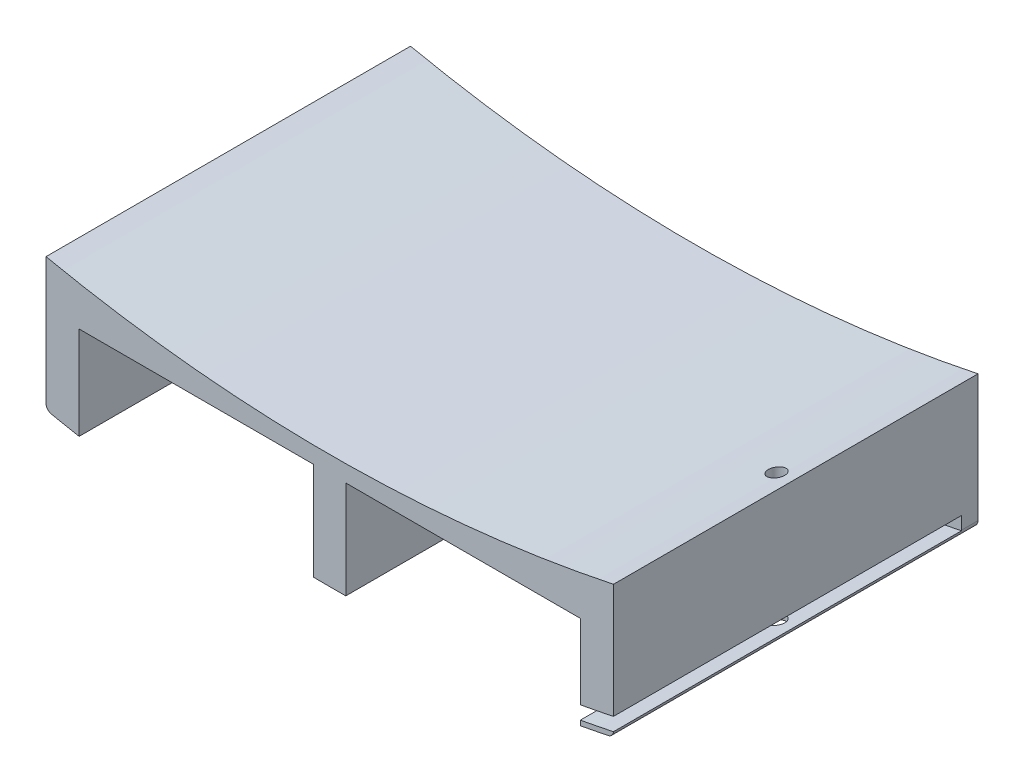
SolidWorks part; units mm, degrees
ref_plane "Front Plane" through (0, 0, 0) normal (0, 0, 1) x (1, 0, 0)
ref_plane "Top Plane" through (0, 0, 0) normal (0, 1, 0) x (1, 0, 0)
ref_plane "Right Plane" through (0, 0, 0) normal (1, 0, 0) x (0, 0, -1)
sketch "ImportedSketch" plane through (0, 0, 0) normal (0, 0, 1) x (1, 0, 0)
  line L9 (-108.7438, 0) -> (-108.7438, -50.8)
  line L11 (-108.7438, 0) -> (-108.7438, 11.3223)
  line L15 (108.7438, 0) -> (108.7438, -50.8)
  line L17 (108.7438, 6.35) -> (108.7438, 0)
  line L18 (108.7438, 6.35) -> (108.7438, 11.3223)
  line L22 (108.7438, 11.3223) -> (108.7438, -50.8)
  line L23 (108.7438, -50.8) -> (-108.7438, -50.8)
  line L24 (108.7438, -50.8) -> (108.7438, 0)
  line L26 (-108.7438, -50.8) -> (-108.7438, 0)
  line L27 (108.7438, -50.8) -> (-108.7438, -50.8)
  line L28 (-108.7438, -50.8) -> (-108.7438, 11.3223)
  arc A0 (-108.7438, 11.3223) -> (108.7438, 11.3223) centre (0, 527.8685) ccw
  point P0 (0, 0)
  point P20 (-108.7438, 11.3223)
sketch "CrossSection" plane through (0, 0, 0) normal (0, 0, 1) x (1, 0, 0)
  line L0 (108.7438, 11.3223) -> (108.7438, -50.8)
  line L1 (108.7438, -50.8) -> (-108.7438, -50.8)
  line L2 (-108.7438, -50.8) -> (-108.7438, 11.3223)
  arc A0 (108.7438, 11.3223) -> (-108.7438, 11.3223) centre (0, 527.8685) cw
extrude "Boss-Extrude2" add sketch "CrossSection" along normal blind 279.4
sketch "Sketch4" plane through (0, 0, 0) normal (0, 0, -1) x (-1, 0, 0)
  line L0 (-108.7438, 11.3223) -> (-108.7437, -39.4777)
  line L1 (108.7438, 11.3223) -> (108.7438, -39.4777)
  line L2 (-108.7437, -39.4777) -> (-108.7438, -50.8)
  line L3 (-108.7438, -50.8) -> (108.7438, -50.8)
  line L4 (108.7438, -50.8) -> (108.7438, -39.4777)
  arc A0 (-108.7438, 11.3223) -> (108.7438, 11.3223) centre (0, 527.8685) ccw
  arc A1 (-108.7437, -39.4777) -> (108.7438, -39.4777) centre (0, 477.0685) ccw
  line M5 (-108.7438, 11.3223) -> (-108.7438, -50.8)
  line M6 (-108.7438, -50.8) -> (108.7438, -50.8)
  line M7 (108.7438, -50.8) -> (108.7438, 11.3223)
  dimension "D1" = 2
extrude "Cut-Extrude1" cut sketch "Sketch4" against normal blind 279.4 contours A1 M5 M6 | A1 L3 M7
fillet "Fillet1" radius 2.54 2 edges at (108.7438, -39.4777, 139.7) (-108.7438, -39.4777, 139.7)
sketch "Sketch5" plane through (0, 0, 279.4) normal (0, 0, 1) x (1, 0, 0)
  line L1 (-108.7438, 11.3223) -> (108.7438, 11.3223)
  line L2 (-108.7438, 11.3223) -> (-108.7438, -50.8)
  line L3 (-108.7438, -50.8) -> (108.7438, -50.8)
  line L4 (108.7438, 11.3223) -> (108.7438, -50.8)
ref_plane "Plane1" through (0, -50.8, 0) normal (0, 1, 0) x (1, 0, 0)
sketch "Sketch7" plane through (0, -50.8, 0) normal (0, 1, 0) x (1, 0, 0)
  line L1 (108.7438, -279.4) -> (-108.7438, -279.4)
  line L2 (108.7438, -279.4) -> (108.7438, 0)
  line L3 (108.7438, 0) -> (-108.7438, 0)
  line L4 (-108.7438, -279.4) -> (-108.7438, 0)
  line L5 (108.7438, -279.4) -> (96.0438, -279.4)
  line L6 (108.7438, -279.4) -> (108.7438, -266.7)
  line L7 (108.7438, -266.7) -> (96.0438, -266.7)
  line L8 (96.0438, -279.4) -> (96.0438, -266.7)
  line L9 (-108.7438, -279.4) -> (-96.0438, -279.4)
  line L10 (-108.7438, -279.4) -> (-108.7438, -266.7)
  line L11 (-108.7438, -266.7) -> (-96.0438, -266.7)
  line L12 (-96.0438, -279.4) -> (-96.0438, -266.7)
  line L13 (-108.7438, 0) -> (-96.0438, 0)
  line L14 (-108.7438, 0) -> (-108.7438, -12.7)
  line L15 (-108.7438, -12.7) -> (-96.0438, -12.7)
  line L16 (-96.0438, 0) -> (-96.0438, -12.7)
  line L17 (108.7438, 0) -> (96.0438, 0)
  line L18 (108.7438, 0) -> (108.7438, -12.7)
  line L19 (108.7438, -12.7) -> (96.0438, -12.7)
  line L20 (96.0438, 0) -> (96.0438, -12.7)
  line L21 (96.0438, -266.7) -> (-96.0438, -266.7)
  line L22 (96.0438, -266.7) -> (96.0438, -12.7)
  line L23 (96.0438, -12.7) -> (-96.0438, -12.7)
  line L24 (-96.0438, -266.7) -> (-96.0438, -12.7)
extrude "Cut-Extrude2" cut sketch "Sketch7" along normal blind 44.45 contours L24 L21 L22 L23
sketch "Sketch8" plane through (0, 0, 12.7) normal (0, 0, 1) x (1, 0, 0)
  line L0 (-96.0438, -41.9891) -> (-96.0438, -6.35)
  line L1 (-96.0438, -6.35) -> (96.0438, -6.35)
  line L2 (96.0438, -6.35) -> (96.0438, -41.9891)
  line L3 (96.0438, -41.9891) -> (-96.0438, -41.9891)
  line L4 (96.0438, -41.9891) -> (-96.0438, -41.9891)
  line L5 (0, -50.8) -> (0, -6.35)
  line L8 (-6.1732, -50.7639) -> (-6.1732, -6.35)
  line L9 (-6.1732, -6.35) -> (6.1732, -6.35)
  line L10 (6.1732, -50.7639) -> (6.1732, -6.35)
  arc A0 (-96.0438, -41.9891) -> (96.0438, -41.9891) centre (0, 477.0685) ccw
  point P11 (0, -41.9891)
extrude "Boss-Extrude3" add sketch "Sketch8" along normal blind 258.064 contours L4 L10 L1 L5 | L8 L4 L5 L1
sketch "Sketch13" plane through (0, 0, 12.7) normal (0, 0, 1) x (1, 0, 0)
  line L0 (0, -50.8) -> (0, -41.9891)
  line L1 (6.1732, -41.9891) -> (-6.1732, -41.9891) construction
  line L2 (-96.0438, -37.5836) -> (-96.0438, -41.9891)
  line L3 (96.0438, -41.9891) -> (96.0438, -37.5836)
  line L4 (-96.0438, -40.1236) -> (-96.0438, -35.0436)
  line L5 (96.0438, -40.1236) -> (96.0438, -35.0436)
  arc A2 (-96.0438, -35.0436) -> (96.0438, -35.0436) centre (0, 484.014) ccw
  arc A3 (-96.0438, -40.1236) -> (96.0438, -40.1236) centre (0, 478.934) ccw
  point P9 (0, -46.3945)
  line M6 (-96.0438, -6.35) -> (-96.0438, -41.9891)
  line M8 (96.0438, -41.9891) -> (96.0438, -6.35)
extrude "Cut-Extrude3" cut sketch "Sketch13" against normal blind 6.35 and the other way blind 260.35 contours A3 L0 A2 M6 | L0 A3 L3 A2 M8
sketch "Sketch14" plane through (0, 0, 266.7) normal (0, 0, -1) x (-1, 0, 0)
  line L0 (96.0438, -35.0436) -> (96.0438, -40.1236)
  line L1 (-150.5419, -27.0129) -> (-150.5419, -21.9329)
  arc A0 (-150.5419, -27.0129) -> (96.0438, -40.1236) centre (0, 478.934) ccw
  arc A1 (-150.5419, -21.9329) -> (96.0438, -35.0436) centre (0, 484.014) ccw
extrude "Cut-Extrude4" cut sketch "Sketch14" against normal blind 6.35 and the other way blind 260.35
sketch "Sketch15" plane through (0, 0, 266.7) normal (0, 0, -1) x (-1, 0, 0)
  line L0 (6.1732, -41.9891) -> (-6.1732, -41.9891)
  line L1 (-6.1732, -6.35) -> (-6.1732, -41.9891) construction
  line L2 (6.1732, -41.9891) -> (-6.1732, -41.9891) construction
  line L3 (6.1732, -41.9891) -> (6.1732, -43.8184)
  line L4 (-6.1732, -41.9891) -> (-6.1732, -43.8184)
  line L5 (6.1732, -41.9891) -> (-6.1732, -41.9891)
  line L6 (6.1732, -43.8184) -> (6.1732, -41.9891)
  line L7 (-6.1732, -41.9891) -> (-6.1732, -43.8184)
  arc A1 (96.0438, -35.0436) -> (-96.0437, -35.0436) centre (0, 484.014) cw
  arc A2 (-96.0438, -35.0436) -> (96.0438, -35.0436) centre (0, 484.014) ccw construction
  arc M2 (-96.0438, -35.0436) -> (96.0438, -35.0436) centre (0, 484.014) ccw
  line M6 (6.1732, -41.9891) -> (-6.1732, -41.9891)
extrude "Boss-Extrude4" add sketch "Sketch15" along normal blind 254 contours L4 L3 M6 M2
sketch "Sketch17" plane through (0, 0, 273.05) normal (0, 0, -1) x (-1, 0, 0)
  line L2 (96.0438, -35.0436) -> (96.0438, -40.1236)
  line L3 (-108.7438, -32.5322) -> (-108.7438, -37.6122)
  arc A0 (96.0438, -35.0436) -> (-108.7438, -32.5322) centre (0, 484.014) cw
  arc A1 (96.0438, -40.1236) -> (-108.7438, -37.6122) centre (0, 478.934) cw
  dimension "D1" = 2
sketch "Sketch18" plane through (0, -50.8, 0) normal (0, 1, 0) x (1, 0, 0)
  line L0 (96.0438, -266.7) -> (106.7173, -279.4)
  line L1 (96.0438, -12.7) -> (106.7173, 0)
  line L3 (96.0438, -139.7) -> (106.7173, -139.7)
  line L4 (96.0438, -266.7) -> (96.0438, -12.7) construction
  line L5 (106.7173, 0) -> (106.7173, -279.4) construction
  circle A0 centre (101.3805, -209.55) radius 3.175
  circle A1 centre (101.3805, -69.85) radius 3.175
  point P16 (101.3805, -69.85)
  point P18 (101.3805, -209.55)
extrude "Cut-Extrude5" cut sketch "Sketch18" along normal blind 71.12 contours A1 | A0
sketch "Sketch19" plane through (108.7438, 0, 0) normal (1, 0, 0) x (0, 0, -1)
  line L0 (-139.7, 11.3223) -> (-139.7, -32.5322) construction
  line L1 (-279.4, 11.3223) -> (0, 11.3223) construction
  line L2 (-6.35, -32.5322) -> (-273.05, -32.5322) construction
sketch "Sketch20" plane through (-108.7438, 0, 0) normal (-1, 0, 0) x (0, 0, 1)
  line L0 (139.7, 11.3223) -> (139.7, -37.4126) construction
  line L1 (279.4, 11.3223) -> (0, 11.3223) construction
  line L2 (0, -37.4126) -> (279.4, -37.4126) construction
ref_plane "Plane3" through (0, 0, 139.7) normal (0, 0, 1) x (1, 0, 0)
split "Split2" trim tools "Plane3" bodies to split 109 resulting bodies 112 113
delete or keep bodies "Body-Delete/Keep 1" type delete bodies bodies 113
sketch "Sketch22" plane through (0, 0, 6.35) normal (0, 0, 1) x (1, 0, 0)
  line L0 (108.7438, -32.5322) -> (108.7358, -37.6139)
  line L1 (-96.0438, -35.0436) -> (-96.0438, -40.1236)
  line L2 (96.0438, -35.0436) -> (96.0438, -40.1236)
  arc A0 (-96.0438, -35.0436) -> (108.7438, -32.5322) centre (0, 484.014) ccw
  arc A1 (108.7358, -37.6139) -> (-96.0438, -40.1236) centre (0, 478.934) cw
